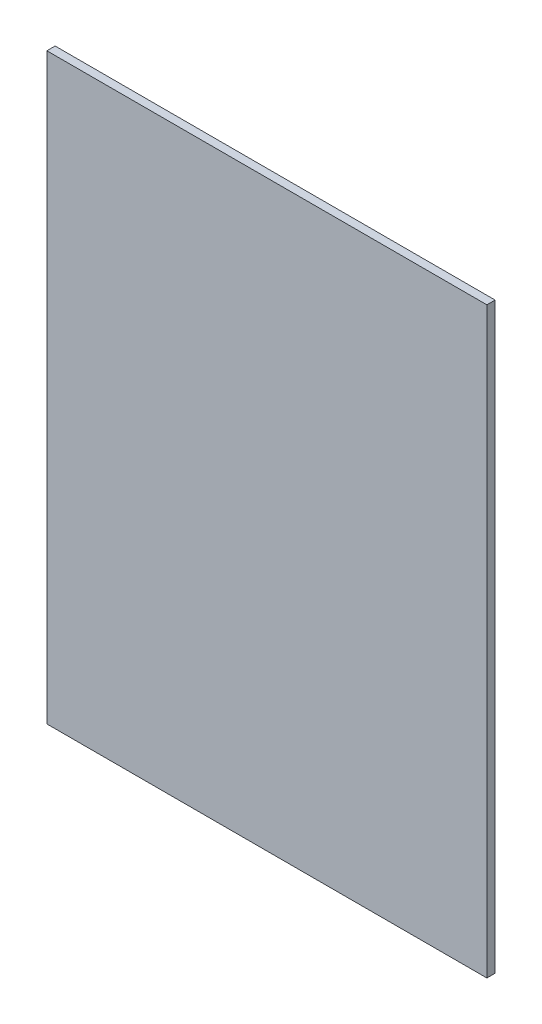
SolidWorks part; units mm, degrees
material "PC High Viscosity"
ref_plane "Front Plane" through (0, 0, 0) normal (0, 0, 1) x (1, 0, 0)
ref_plane "Top Plane" through (0, 0, 0) normal (0, 1, 0) x (1, 0, 0)
ref_plane "Right Plane" through (0, 0, 0) normal (1, 0, 0) x (0, 0, -1)
sketch "Sketch1" plane through (0, 0, 0) normal (0, 0, 1) x (1, 0, 0)
  line L1 (-80, -106) -> (80, -106)
  line L2 (-80, -106) -> (-80, 106)
  line L3 (-80, 106) -> (80, 106)
  line L4 (80, -106) -> (80, 106)
  line L5 (-80, -106) -> (80, 106) construction
  line L6 (-80, 106) -> (80, -106) construction
  point P0 (0, 0)
  dimension "D1" = 160
  dimension "D2" = 212
extrude "Boss-Extrude1" add sketch "Sketch1" along normal mid plane 3
sketch "Sketch2" [suppressed] plane through (0, 0, 2.5) normal (0, 0, 1) x (1, 0, 0)
  line L0 (106, 171) -> (104, 171) construction
  line L1 (-155.214, 211.8255) -> (203.9552, 211.8255)
  line L2 (-155.214, 211.8255) -> (-155.214, 171)
  line L3 (-155.214, 171) -> (203.9552, 171)
  line L4 (203.9552, 211.8255) -> (203.9552, 171)
extrude "Cut-Extrude1" [suppressed] cut sketch "Sketch2" against normal through all
